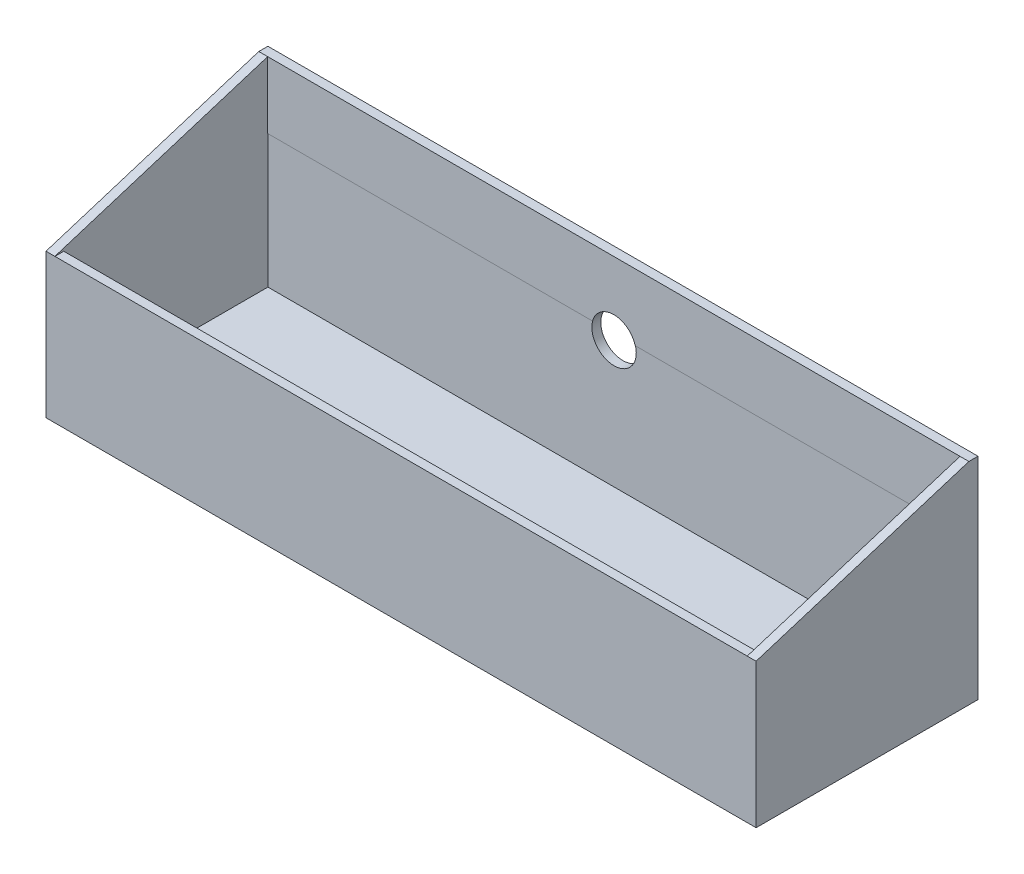
SolidWorks part; units mm, degrees
ref_plane "Front" through (0, 0, 0) normal (0, 0, 1) x (1, 0, 0)
ref_plane "Top" through (0, 0, 0) normal (0, 1, 0) x (1, 0, 0)
ref_plane "Right" through (0, 0, 0) normal (1, 0, 0) x (0, 0, -1)
sketch "Sketch1" plane through (0, 0, 0) normal (0, 1, 0) x (1, 0, 0)
  line L1 (0, 0) -> (160, 0)
  line L2 (0, 0) -> (0, -50)
  line L3 (0, -50) -> (160, -50)
  line L4 (160, 0) -> (160, -50)
  dimension "D1" = 160
  dimension "D2" = 50
extrude "Boss-Extrude1" add sketch "Sketch1" along normal blind 2.5
sketch "Sketch2" plane through (0, 2.5, 0) normal (0, 1, 0) x (1, 0, 0)
  line L0 (0, 0) -> (0, -50) construction
  circle A0 centre (15, -25) radius 3.75
  circle A1 centre (36, -25) radius 3.75
  circle A2 centre (57, -25) radius 3.75
  circle A3 centre (78, -25) radius 3.75
  circle A4 centre (99, -25) radius 3.75
  circle A5 centre (120, -25) radius 3.75
  circle A6 centre (141, -25) radius 3.75
  dimension "D1" = 7.5
  dimension "D2" = 15
  dimension "D3" = 7
extrude "Cut-Extrude1" cut sketch "Sketch2" against normal through all
sketch "Sketch3" plane through (0, 2.5, 0) normal (0, 1, 0) x (1, 0, 0)
  line L0 (2, -2) -> (2, -48)
  line L1 (0, 0) -> (160, 0)
  line L2 (0, 0) -> (0, -50)
  line L3 (0, -50) -> (160, -50)
  line L4 (160, 0) -> (160, -50)
  line L5 (2, -48) -> (158, -48)
  line L6 (158, -2) -> (158, -48)
  line L7 (2, -2) -> (158, -2)
  dimension "D1" = 2
extrude "Boss-Extrude2" add sketch "Sketch3" along normal blind 30
sketch "Sketch5" plane through (0, 32.5, 0) normal (0, 1, 0) x (1, 0, 0)
  line L0 (160, -50) -> (160, 0) construction
  line L1 (0, 0) -> (160, 0)
  line L2 (0, 0) -> (0, -2.05)
  line L3 (0, -2.05) -> (160, -2.05)
  line L4 (160, 0) -> (160, -2.05)
extrude "Boss-Extrude4" add sketch "Sketch5" along normal blind 15
sketch "Sketch6" plane through (160, 0, 0) normal (1, 0, 0) x (0, 0, -1)
  line L0 (-2.05, 32.5) -> (-50, 32.5)
  line L2 (-50, 32.5) -> (-2.05, 47.5)
  line L3 (-2.05, 47.5) -> (-2.05, 32.5)
extrude "Boss-Extrude5" add sketch "Sketch6" against normal blind 2
sketch "Sketch8" plane through (0, 0, 0) normal (-1, 0, 0) x (0, 0, 1)
  line L0 (2.05, 47.5) -> (2.05, 32.5)
  line L1 (2.05, 32.5) -> (50, 32.5)
  line L2 (50, 32.5) -> (2.05, 47.5)
extrude "Boss-Extrude7" add sketch "Sketch8" against normal blind 2
sketch "Sketch9" plane through (0, 0, 0) normal (0, 0, -1) x (-1, 0, 0)
  circle A0 centre (-80, 31.1534) radius 5
  dimension "D1" = 10
extrude "Cut-Extrude2" cut sketch "Sketch9" against normal blind 3
